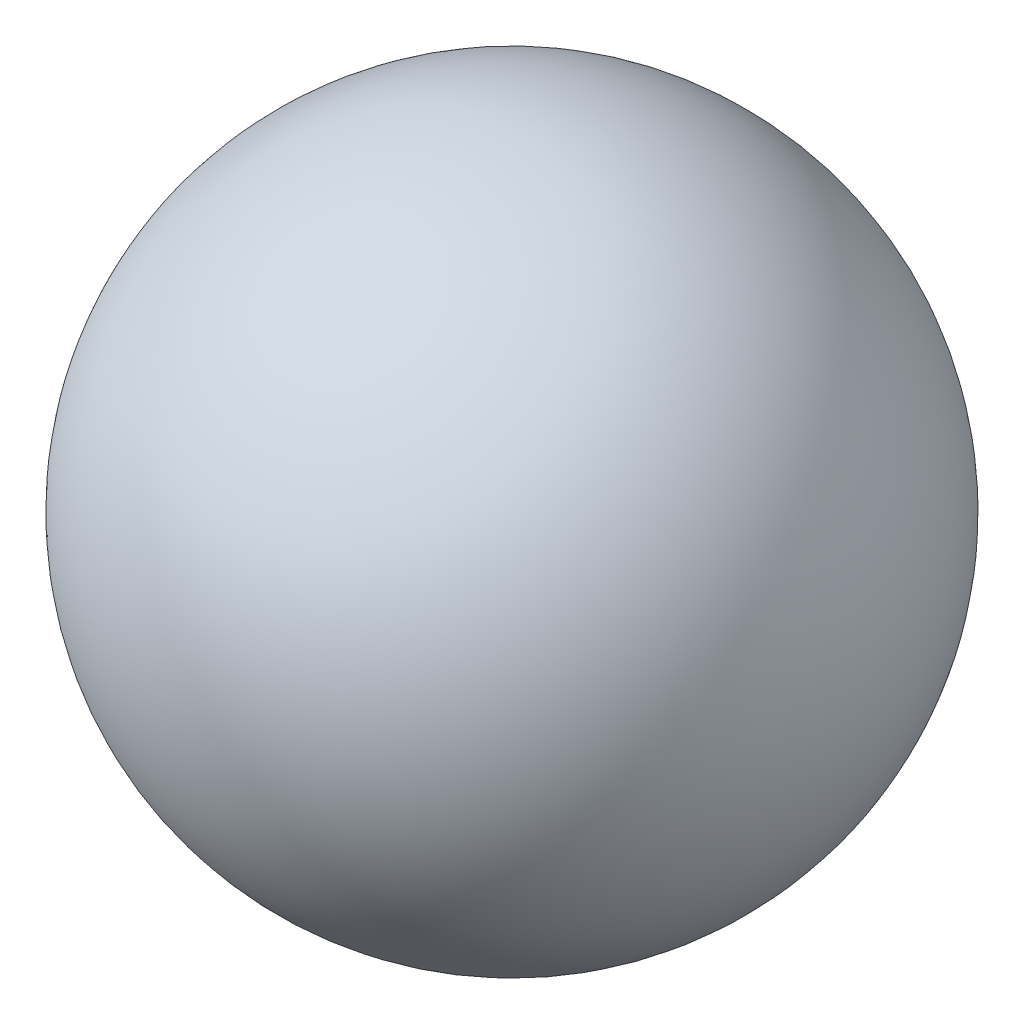
SolidWorks part; units mm, degrees
ref_plane "Front Plane" through (0, 0, 0) normal (0, 0, 1) x (1, 0, 0)
ref_plane "Top Plane" through (0, 0, 0) normal (0, 1, 0) x (1, 0, 0)
ref_plane "Right Plane" through (0, 0, 0) normal (1, 0, 0) x (0, 0, -1)
sketch "Sketch1" plane through (0, 0, 0) normal (0, 0, 1) x (1, 0, 0)
  line L0 (-12, 0) -> (12, 0)
  arc A0 (-12, 0) -> (12, 0) centre (0, 0) ccw
  dimension "D1" = 24
revolve "Revolve1" add sketch "Sketch1" angle 360 about L0
